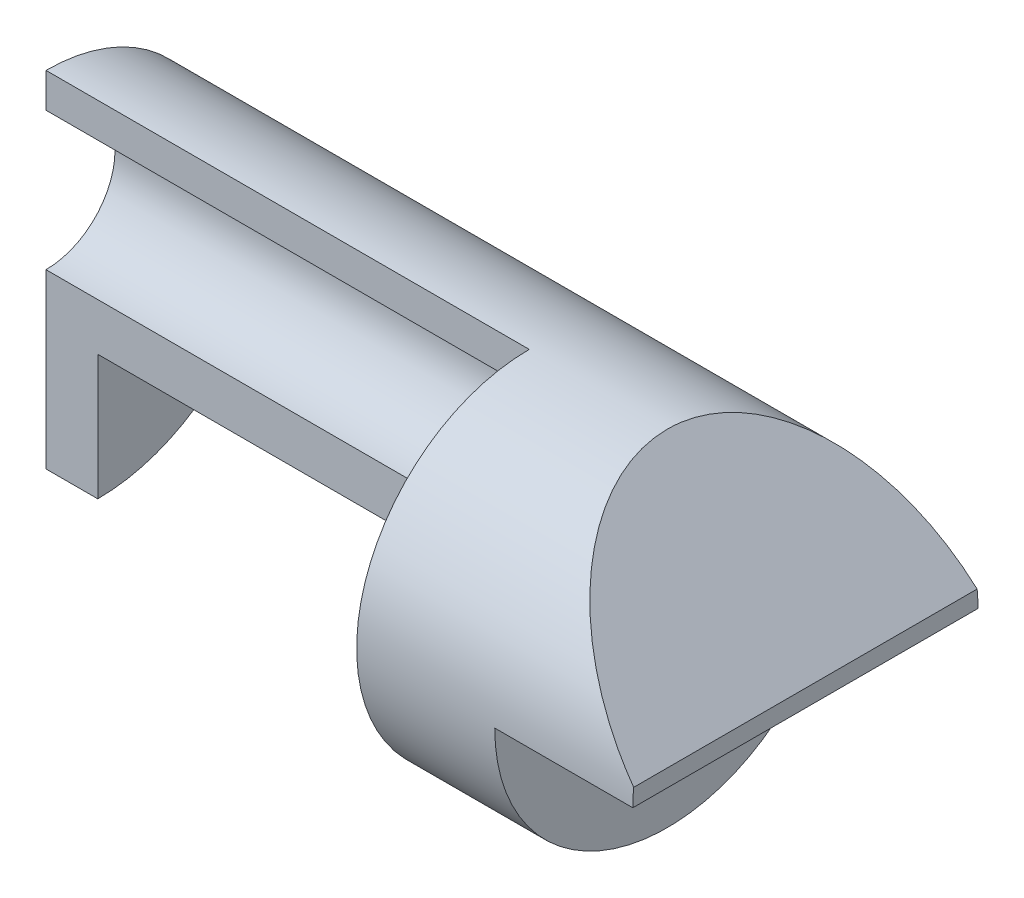
SolidWorks part; units mm, degrees
ref_plane "前视基准面" through (0, 0, 0) normal (0, 0, 1) x (1, 0, 0)
ref_plane "上视基准面" through (0, 0, 0) normal (0, 1, 0) x (1, 0, 0)
ref_plane "右视基准面" through (0, 0, 0) normal (1, 0, 0) x (0, 0, -1)
other "Configuration Table"
sketch "草图1" plane through (0, 0, 0) normal (0, 0, 1) x (1, 0, 0)
  line L0 (0, 0) -> (0, 5)
  line L1 (0, 5) -> (22, 5)
  line L2 (22, 5) -> (22, 0)
  line L3 (22, 0) -> (0, 0)
  dimension "D1" = 5
  dimension "D2" = 22
revolve "旋转1" add sketch "草图1" angle 360 about L3
sketch "草图3" plane through (0, 0, 0) normal (0, 0, 1) x (1, 0, 0)
  line L0 (18, -5) -> (18, 0)
  line L1 (0, -5) -> (22, -5) construction
  line L2 (18, 0) -> (22, 0)
  line L3 (22, -5) -> (22, 5) construction
  line L4 (22, 0) -> (22, 0.5)
  line L5 (22, 0.5) -> (18, 5)
  line L6 (18, 5) -> (22, 5)
  line L7 (22, 5) -> (22, 0.5)
  line L8 (22, 0) -> (22, -5)
  line L9 (22, -5) -> (18, -5)
  point P4 (22, 0.25)
  dimension "D1" = 4
  dimension "D2" = 4
  dimension "D3" = 0.5
  dimension "D4" = 5
extrude "切除-拉伸1" cut sketch "草图3" against normal through all both and the other way through all contours L8 L9 L0 L2 | L5 L6 L7
sketch "草图4" plane through (0, 0, 0) normal (0, 1, 0) x (1, 0, 0)
  line L2 (14, 0) -> (14, -5)
  line L3 (0, -5) -> (18, -5) construction
  line L6 (22, 4.9749) -> (22, -4.9749) construction
  line L7 (14, -5) -> (0, -5)
  line L8 (0, 0) -> (14, 0)
  line L9 (14, -5) -> (0, -5)
  line L10 (0, -5) -> (0, 0)
  dimension "D1" = 8
extrude "切除-拉伸4" cut sketch "草图4" against normal through all both and the other way through all contours L10 L7 L2 L8
sketch "草图5" plane through (0, 0, 0) normal (-1, 0, 0) x (0, 0, 1)
  line L0 (0, -5) -> (0, 5) construction
  circle A0 centre (0, 2) radius 2
  dimension "D1" = 4
extrude "切除-拉伸5" cut sketch "草图5" against normal blind 16 and the other way through all
sketch "草图6" plane through (0, 0, 0) normal (0, 0, 1) x (1, 0, 0)
  line L0 (1.5, -5) -> (1.5, -1.3721)
  line L1 (0, -5) -> (14, -5) construction
  line L2 (1.5, -1.3721) -> (12, -1.3721)
  line L3 (12, -1.3721) -> (12, -5)
  line L4 (0, -5) -> (0, 0) construction
  line L5 (1.5, -5) -> (12, -5)
  dimension "D1" = 6
  dimension "D2" = 1.5
extrude "切除-拉伸6" cut sketch "草图6" against normal blind 16 contours L5 L3 L2 L0
